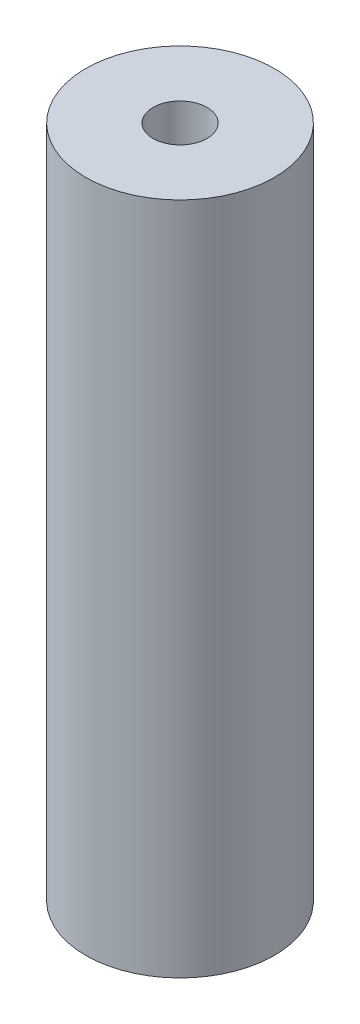
SolidWorks part; units mm, degrees
material "Brass"
ref_plane "Front Plane" through (0, 0, 0) normal (0, 0, 1) x (1, 0, 0)
ref_plane "Top Plane" through (0, 0, 0) normal (0, 1, 0) x (1, 0, 0)
ref_plane "Right Plane" through (0, 0, 0) normal (1, 0, 0) x (0, 0, -1)
sketch "Sketch1" plane through (0, 0, 0) normal (0, 1, 0) x (1, 0, 0)
  circle A0 centre (0, 0) radius 2
  circle A1 centre (0, 0) radius 7
  dimension "D1" = 4
  dimension "D2" = 14
extrude "Boss-Extrude1" add sketch "Sketch1" along normal blind 50
